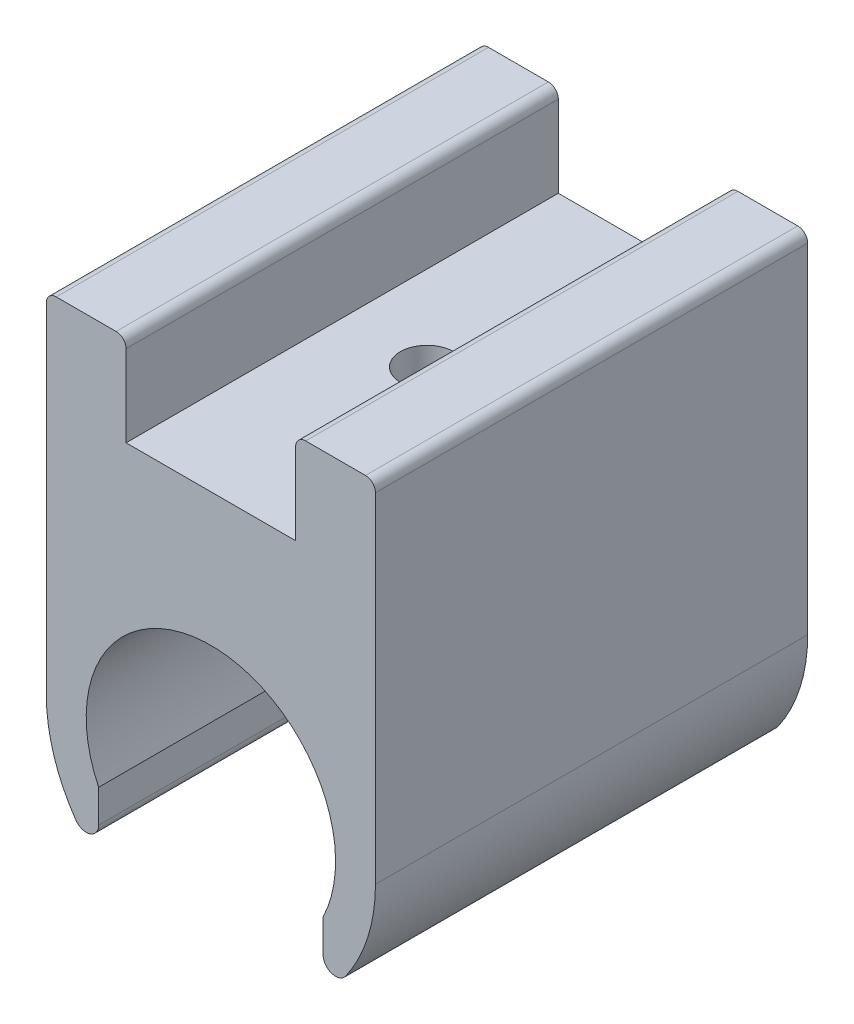
SolidWorks part; units mm, degrees
material "ABS"
ref_plane "Płaszczyzna przednia" through (0, 0, 0) normal (0, 0, 1) x (1, 0, 0)
ref_plane "Płaszczyzna górna" through (0, 0, 0) normal (0, 1, 0) x (1, 0, 0)
ref_plane "Płaszczyzna prawa" through (0, 0, 0) normal (1, 0, 0) x (0, 0, -1)
sketch "Szkic1" plane through (0, 0, 0) normal (0, 0, 1) x (1, 0, 0)
  line L0 (0, 0) -> (0, -7.5) construction
  line L1 (-6.75, -3.2692) -> (-6.75, -7.2421)
  line L2 (6.75, -3.2692) -> (6.75, -7.2421)
  line L3 (9.9, 0) -> (9.9, 15.5)
  line L4 (9.9, 15.5) -> (-9.9, 15.5)
  line L5 (-9.9, 15.5) -> (-9.9, 0)
  arc A0 (6.75, -3.2692) -> (-6.75, -3.2692) centre (0, 0) ccw
  arc A1 (-9.9, 0) -> (-6.75, -7.2421) centre (0, 0) ccw
  arc A2 (6.75, -7.2421) -> (9.9, 0) centre (0, 0) ccw
  dimension "D1" = 15
  dimension "D2" = 13.5
  dimension "D3" = 2.4
  dimension "D4" = 15.5
extrude "Dodanie-wyciągnięcie1" add sketch "Szkic1" along normal blind 26
sketch "Szkic2" plane through (0, 15.5, 0) normal (0, 1, 0) x (1, 0, 0)
  line L0 (0, 0) -> (0, -26) construction
  line L1 (9.9, -26) -> (-9.9, -26) construction
  line L2 (0, 0) -> (0, -26) construction
  line L3 (-5.1, 0) -> (-5.1, -26)
  line L5 (5.1, -26) -> (5.1, 0)
  line L7 (9.9, 0) -> (-9.9, 0) construction
  line L12 (5.1, 0) -> (9.9, 0)
  line L13 (9.9, 0) -> (9.9, -26)
  line L14 (-5.1, -26) -> (-9.9, -26)
  line L15 (-9.9, -26) -> (-9.9, 0)
  line L16 (-9.9, 0) -> (-5.1, 0)
  line L17 (9.9, -26) -> (5.1, -26)
  point P8 (0, -13)
  dimension "D2" = 10.2
extrude "Dodanie-wyciągnięcie2" add sketch "Szkic2" along normal blind 5.5
fillet "Zaokrąglenie1" radius 0.75 2 edges at (6.75, -7.2421, 13) (-6.75, -7.2421, 13)
sketch "Szkic6" plane through (0, 15.5, 0) normal (0, 1, 0) x (1, 0, 0)
  line L0 (0, 0) -> (0, -26) construction
  line L1 (5.1, -26) -> (-5.1, -26) construction
  circle A0 centre (0, -13) radius 1.6
  dimension "D1" = 3.2
extrude "Wytnij-wyciągnięcie3" cut sketch "Szkic6" against normal blind 2.5
sketch "Szkic7" plane through (0, 13, 0) normal (0, 1, 0) x (1, 0, 0)
  line L0 (0, -13) -> (0, -16) construction
  line L1 (3, 0) -> (-3, 0)
  line L2 (3, 0) -> (3, -16)
  line L3 (3, -16) -> (-3, -16)
  line L4 (-3, 0) -> (-3, -16)
  dimension "D1" = 6
  dimension "D2" = 3
extrude "Wytnij-wyciągnięcie4" cut sketch "Szkic7" against normal blind 2.4
sketch "Szkic8" plane through (0, 10.6, 0) normal (0, 1, 0) x (1, 0, 0)
  circle A0 centre (0, -13) radius 1.6 construction
  circle A1 centre (0, -13) radius 1.6
extrude "Wytnij-wyciągnięcie5" cut sketch "Szkic8" against normal blind 2
fillet "Zaokrąglenie2" radius 0.6 4 edges at (-9.9, 21, 13) (-5.1, 21, 13) (5.1, 21, 13) (9.9, 21, 13)
equation "\"D2@Szkic7\"=\"D1@Szkic7\"/2"
